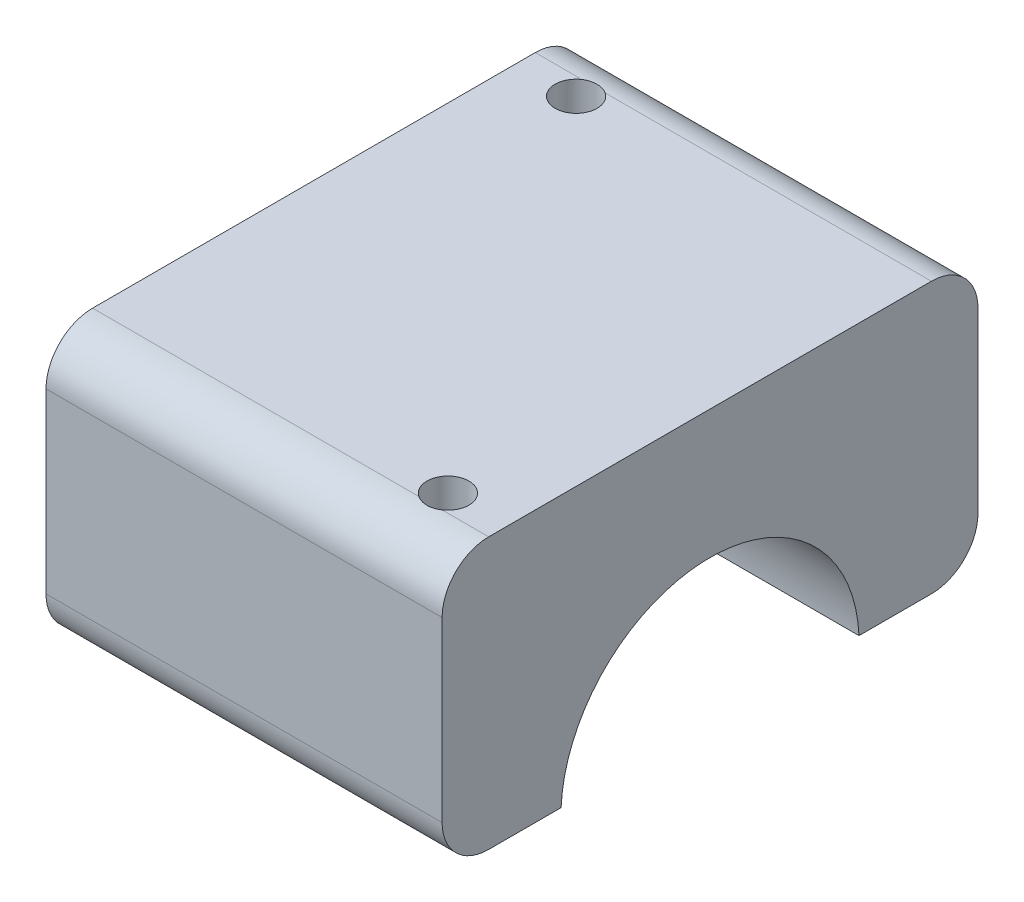
SolidWorks part; units mm, degrees
ref_plane "Front Plane" through (0, 0, 0) normal (0, 0, 1) x (1, 0, 0)
ref_plane "Top Plane" through (0, 0, 0) normal (0, 1, 0) x (1, 0, 0)
ref_plane "Right Plane" through (0, 0, 0) normal (1, 0, 0) x (0, 0, -1)
sketch "Sketch1" plane through (0, 0, 0) normal (1, 0, 0) x (0, 0, -1)
  line L0 (-19, 0.6) -> (19, 0.6)
  line L1 (23, 4.6) -> (23, 19.84)
  line L2 (19, 23.84) -> (-19, 23.84)
  line L3 (-23, 19.84) -> (-23, 4.6)
  arc A0 (19, 0.6) -> (23, 4.6) centre (19, 4.6) ccw
  arc A1 (23, 19.84) -> (19, 23.84) centre (19, 19.84) ccw
  arc A2 (-19, 23.84) -> (-23, 19.84) centre (-19, 19.84) ccw
  arc A3 (-23, 4.6) -> (-19, 0.6) centre (-19, 4.6) ccw
extrude "Boss-Extrude1" add sketch "Sketch1" along normal mid plane 34
sketch "Sketch2" plane through (0, 0, 0) normal (1, 0, 0) x (0, 0, -1)
  circle A0 centre (0, 0) radius 12.8
extrude "Cut-Extrude1" cut sketch "Sketch2" against normal through all and the other way through all
ref_plane "Plane1" through (0, 0.6, 0) normal (0, 1, 0) x (1, 0, 0)
sketch "Sketch3" plane through (0, 0.6, 0) normal (0, 1, 0) x (1, 0, 0)
  circle A0 centre (12, -17.5) radius 1.8
  circle A1 centre (-12, 17.5) radius 1.8
extrude "Cut-Extrude2" cut sketch "Sketch3" along normal blind 23.84
